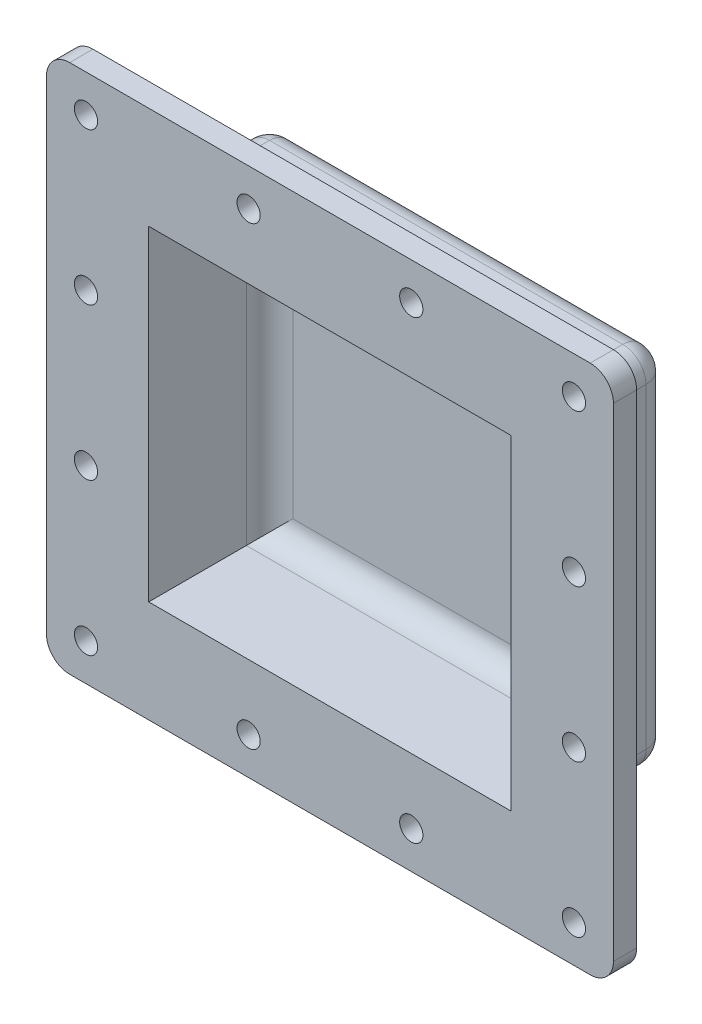
SolidWorks part; units mm, degrees
ref_plane "Front Plane" through (0, 0, 0) normal (0, 0, 1) x (1, 0, 0)
ref_plane "Top Plane" through (0, 0, 0) normal (0, 1, 0) x (1, 0, 0)
ref_plane "Right Plane" through (0, 0, 0) normal (1, 0, 0) x (0, 0, -1)
sketch "Sketch1" plane through (0, 0, 0) normal (0, 0, 1) x (1, 0, 0)
  line L1 (-21.5, 19.5) -> (21.5, 19.5)
  line L2 (-21.5, 19.5) -> (-21.5, -19.5)
  line L3 (-21.5, -19.5) -> (21.5, -19.5)
  line L4 (21.5, 19.5) -> (21.5, -19.5)
  line L5 (-21.5, 19.5) -> (21.5, -19.5) construction
  line L6 (-21.5, -19.5) -> (21.5, 19.5) construction
  point P0 (0, 0)
  dimension "D1" = 43
  dimension "D2" = 39
extrude "Boss-Extrude1" add sketch "Sketch1" along normal blind 12.5
shell "Shell1" thickness 2
sketch "Sketch2" plane through (0, 0, 12.5) normal (0, 0, 1) x (1, 0, 0)
  line L0 (-21.5, 19.5) -> (-21.5, -19.5) construction
  line L1 (-30.5, 28.5) -> (30.5, 28.5)
  line L2 (-30.5, 28.5) -> (-30.5, -28.5)
  line L3 (-30.5, -28.5) -> (30.5, -28.5)
  line L4 (30.5, 28.5) -> (30.5, -28.5)
  line L5 (-30.5, 28.5) -> (30.5, -28.5) construction
  line L6 (-30.5, -28.5) -> (30.5, 28.5) construction
  line L7 (-21.5, 19.5) -> (21.5, 19.5) construction
  line L8 (19.5, -17.5) -> (19.5, 17.5) construction
  line L9 (-19.5, -17.5) -> (19.5, -17.5)
  line L10 (-19.5, -17.5) -> (-19.5, 17.5)
  line L11 (-19.5, 17.5) -> (19.5, 17.5)
  line L12 (19.5, -17.5) -> (19.5, 17.5)
  line L13 (-19.5, -17.5) -> (19.5, 17.5) construction
  line L14 (-19.5, 17.5) -> (19.5, -17.5) construction
  line L15 (19.5, -17.5) -> (19.5, 17.5) construction
  point P0 (0, 0)
  point P10 (0, 0)
  dimension "D1" = 9
  dimension "D2" = 9
extrude "Boss-Extrude2" add sketch "Sketch2" along normal blind 2.5
fillet "Fillet1" radius 2.5 4 edges at (-30.5, -28.5, 13.75) (30.5, -28.5, 13.75) (30.5, 28.5, 13.75) (-30.5, 28.5, 13.75)
fillet "Fillet2" radius 2.5 12 edges at (19.5, 0, 2) (0, 17.5, 2) (-19.5, 0, 2) (0, -17.5, 2) (0, -19.5, 0) (-21.5, 0, 0) (0, 19.5, 0) (21.5, 0, 0) (21.5, -19.5, 6.25) (-21.5, -19.5, 6.25) (-21.5, 19.5, 6.25) (21.5, 19.5, 6.25)
sketch "Sketch3" plane through (0, 0, 2) normal (0, 0, 1) x (1, 0, 0)
  line L1 (-7.5, 14) -> (7.5, 14)
  line L2 (-7.5, 14) -> (-7.5, 6)
  line L3 (-7.5, 6) -> (7.5, 6)
  line L4 (7.5, 14) -> (7.5, 6)
  line L5 (-7.5, 14) -> (7.5, 6) construction
  line L6 (-7.5, 6) -> (7.5, 14) construction
  point P0 (0, 10)
  dimension "D1" = 8
  dimension "D2" = 15
  dimension "D3" = 10
extrude "Cut-Extrude1" cut sketch "Sketch3" against normal through all
sketch "Sketch4" plane through (0, 0, 15) normal (0, 0, 1) x (1, 0, 0)
  line L1 (-21.5, 19.5) -> (-21.5, -19.5) construction
  line L2 (-21.5, 19.5) -> (21.5, 19.5) construction
  line L3 (-26.25, 24.5) -> (26.25, 24.5) construction
  line L10 (-26.25, 24.5) -> (-26.25, -24.5) construction
  line L11 (-26.25, -24.5) -> (26.25, -24.5) construction
  line L18 (26.25, 24.5) -> (26.25, -24.5) construction
  line L19 (-26.25, 24.5) -> (26.25, -24.5) construction
  line L20 (-26.25, -24.5) -> (26.25, 24.5) construction
  circle A21 centre (-26.25, 24.5) radius 1.25
  circle A25 centre (-8.75, 24.5) radius 1.25
  circle A26 centre (8.75, 24.5) radius 1.25
  circle A27 centre (26.25, 24.5) radius 1.25
  circle A30 centre (26.25, 8.1667) radius 1.25
  circle A33 centre (26.25, -8.1667) radius 1.25
  circle A34 centre (-8.75, -24.5) radius 1.25
  circle A35 centre (8.75, -24.5) radius 1.25
  circle A36 centre (26.25, -24.5) radius 1.25
  circle A37 centre (-26.25, 8.1667) radius 1.25
  circle A38 centre (-26.25, -8.1667) radius 1.25
  circle A39 centre (-26.25, -24.5) radius 1.25
  circle A40 centre (-8.75, 8.1667) radius 1.25 [skipped]
  circle A41 centre (8.75, 8.1667) radius 1.25 [skipped]
  circle A42 centre (-8.75, -8.1667) radius 1.25 [skipped]
  circle A43 centre (8.75, -8.1667) radius 1.25 [skipped]
  point P0 (0, 0)
  dimension "D1" = 4.75
  dimension "D3" = 2.5
  dimension "D2" = 5
  dimension "D5" = 4
  dimension "D4" = 4
extrude "Cut-Extrude2" cut sketch "Sketch4" against normal up to surface (2.5 mm away) up to face at (0, 0, 12.5)
equation "\"case_width\"=43.00"
equation "\"D1@Sketch1\"=\"case_width\""
